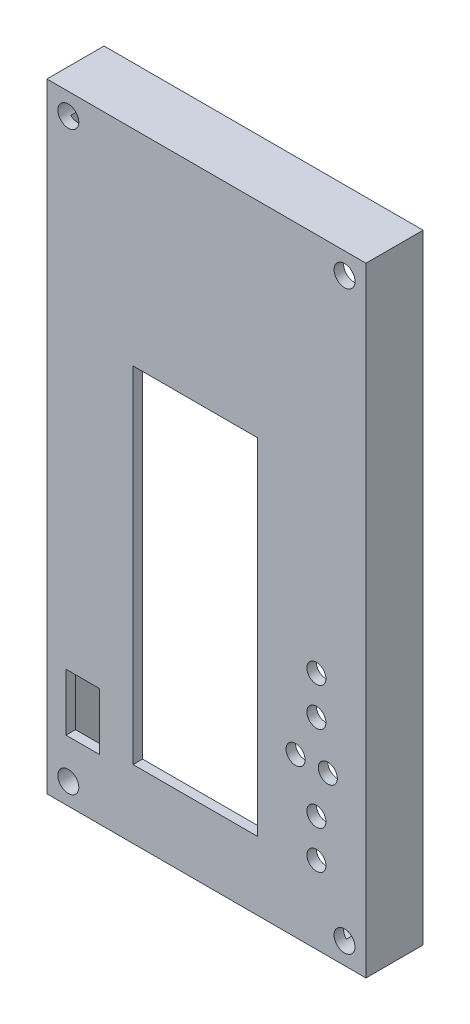
SolidWorks part; units mm, degrees
ref_plane "Front Plane" through (0, 0, 0) normal (0, 0, 1) x (1, 0, 0)
ref_plane "Top Plane" through (0, 0, 0) normal (0, 1, 0) x (1, 0, 0)
ref_plane "Right Plane" through (0, 0, 0) normal (1, 0, 0) x (0, 0, -1)
sketch "Sketch1" plane through (0, 0, 0) normal (0, 0, 1) x (1, 0, 0)
  line L0 (-33.5, -68.3325) -> (33.5, -68.3325)
  line L1 (-33.5, -68.3325) -> (-33.5, 61.6675)
  line L2 (-33.5, 61.6675) -> (33.5, 61.6675)
  line L3 (33.5, -68.3325) -> (33.5, 61.6675)
  line L4 (-30.5, -65.3325) -> (30.5, -65.3325)
  line L5 (30.5, -65.3325) -> (30.5, 58.6675)
  line L6 (-30.5, 58.6675) -> (30.5, 58.6675)
  line L7 (-30.5, -65.3325) -> (-30.5, 58.6675)
  dimension "D1" = 3
extrude "Boss-Extrude1" add sketch "Sketch1" along normal blind 10
sketch "Sketch2" plane through (0, 0, 10) normal (0, 0, 1) x (1, 0, 0)
  line L1 (-33.5, -68.3325) -> (33.5, -68.3325)
  line L2 (-33.5, -68.3325) -> (-33.5, 61.6675)
  line L3 (-33.5, 61.6675) -> (33.5, 61.6675)
  line L4 (33.5, -68.3325) -> (33.5, 61.6675)
  line L5 (-15.4, -53.9675) -> (10.7, -53.9675)
  line L6 (-15.4, -53.9675) -> (-15.4, 18.5325)
  line L7 (-15.4, 18.5325) -> (10.7, 18.5325)
  line L8 (10.7, -53.9675) -> (10.7, 18.5325)
  line L9 (-29.5, -55.6675) -> (-22.5, -55.6675)
  line L10 (-29.5, -55.6675) -> (-29.5, -43.6675)
  line L11 (-29.5, -43.6675) -> (-22.5, -43.6675)
  line L12 (-22.5, -55.6675) -> (-22.5, -43.6675)
  dimension "D1" = 18.1
  dimension "D2" = 105.335
  dimension "D3" = 117.335
  dimension "D4" = 43.135
  dimension "D5" = 115.635
extrude "Boss-Extrude2" add sketch "Sketch2" along normal blind 2
sketch "Sketch3" plane through (0, 0, 12) normal (0, 0, 1) x (1, 0, 0)
  circle A0 centre (23.0965, -52.1196) radius 2
  circle A1 centre (23.0965, -44.1155) radius 2
  circle A3 centre (18.7156, -35.0638) radius 2
  circle A4 centre (23.0964, -26.1155) radius 2
  circle A5 centre (23.0964, -18.1155) radius 2
  circle A6 centre (25.4965, -35.0661) radius 2
extrude "Cut-Extrude1" cut sketch "Sketch3" against normal through all
sketch "Sketch4" plane through (0, 0, 12) normal (0, 0, 1) x (1, 0, 0)
  line L0 (-33.5, 61.6675) -> (-33.5, -68.3325) construction
  line L1 (33.5, 61.6675) -> (-33.5, 61.6675) construction
  line L3 (33.5, -68.3325) -> (33.5, 61.6675) construction
  line L4 (-33.5, -68.3325) -> (33.5, -68.3325) construction
  circle A0 centre (-29, 57.1675) radius 2.2
  circle A1 centre (29, 57.1675) radius 2.2
  circle A2 centre (-29, -63.8325) radius 2.2
  circle A3 centre (29, -63.8325) radius 2.2
  dimension "D1" = 4.5
  dimension "D5" = 4.5
  dimension "D2" = 4.5
  dimension "D3" = 4.5
  dimension "D4" = 4.5
extrude "Cut-Extrude2" cut sketch "Sketch4" against normal through all
